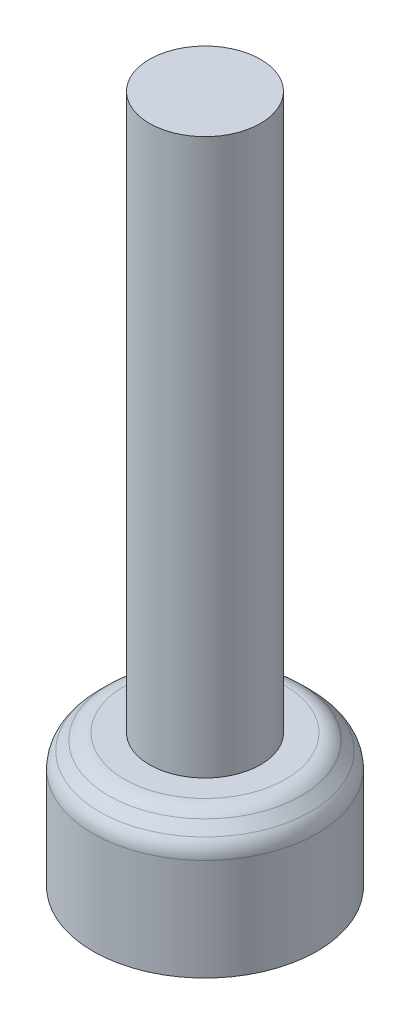
SolidWorks part; units mm, degrees
ref_plane "Front Plane" through (0, 0, 0) normal (0, 0, 1) x (1, 0, 0)
ref_plane "Top Plane" through (0, 0, 0) normal (0, 1, 0) x (1, 0, 0)
ref_plane "Right Plane" through (0, 0, 0) normal (1, 0, 0) x (0, 0, -1)
sketch "Sketch2" plane through (0, 0, 0) normal (0, 1, 0) x (1, 0, 0)
  circle A0 centre (0, 0) radius 5
extrude "Boss-Extrude1" add sketch "Sketch2" along normal blind 50
sketch "Sketch3" plane through (0, 0, 0) normal (0, -1, 0) x (1, 0, 0)
  circle A0 centre (0, 0) radius 10.0876
extrude "Boss-Extrude2" add sketch "Sketch3" along normal blind 12
chamfer "Chamfer1" distance 2 angle 45 1 edges at (0, 0, -10.0876)
fillet "Fillet2" radius 2 1 edges at (0, 0, -8.0876)
fillet "Fillet3" radius 2 1 edges at (0, -2, -10.0876)
